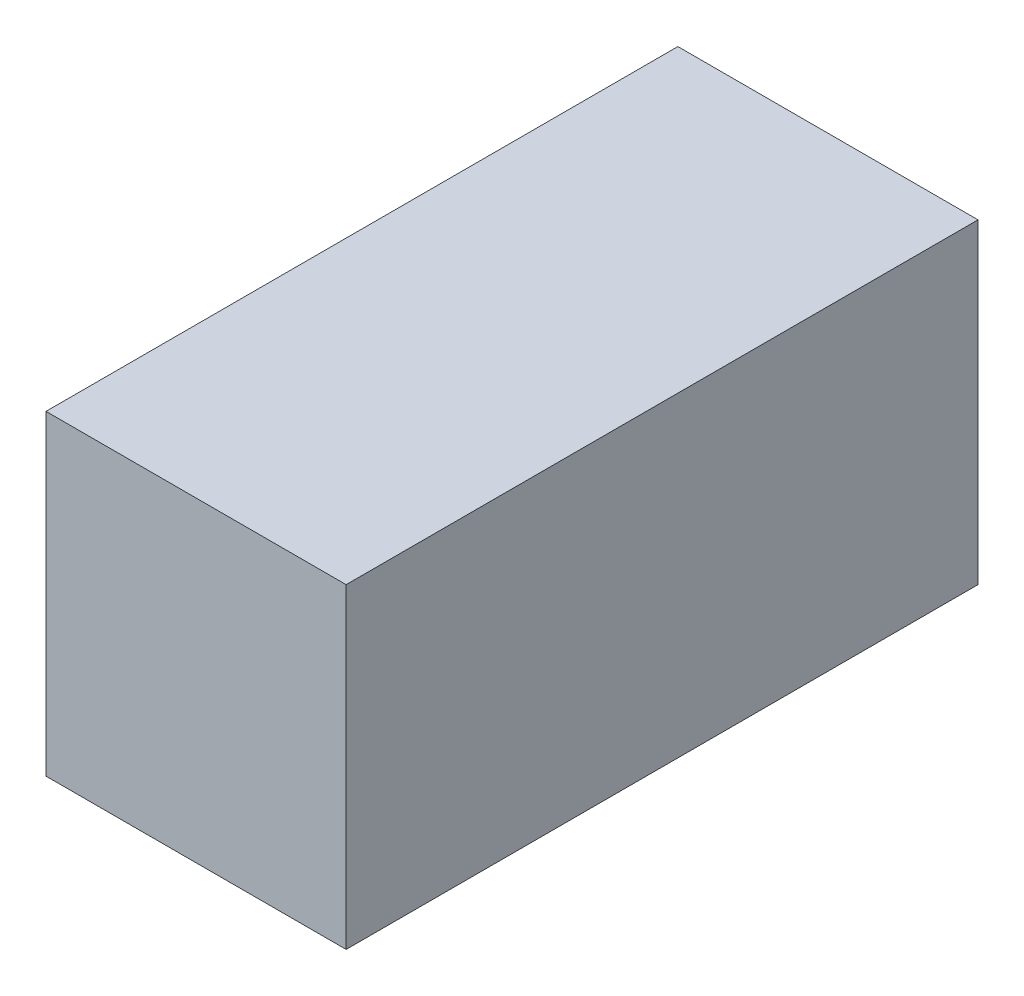
SolidWorks part; units mm, degrees
ref_plane "Front Plane" through (0, 0, 0) normal (0, 0, 1) x (1, 0, 0)
ref_plane "Top Plane" through (0, 0, 0) normal (0, 1, 0) x (1, 0, 0)
ref_plane "Right Plane" through (0, 0, 0) normal (1, 0, 0) x (0, 0, -1)
sketch "Sketch1" plane through (0, 0, 0) normal (1, 0, 0) x (0, 0, -1)
  line L1 (0, 0) -> (40, 0)
  line L2 (0, 0) -> (0, 20)
  line L3 (0, 20) -> (40, 20)
  line L4 (40, 0) -> (40, 20)
extrude "Boss-Extrude1" add sketch "Sketch1" along normal blind 19
